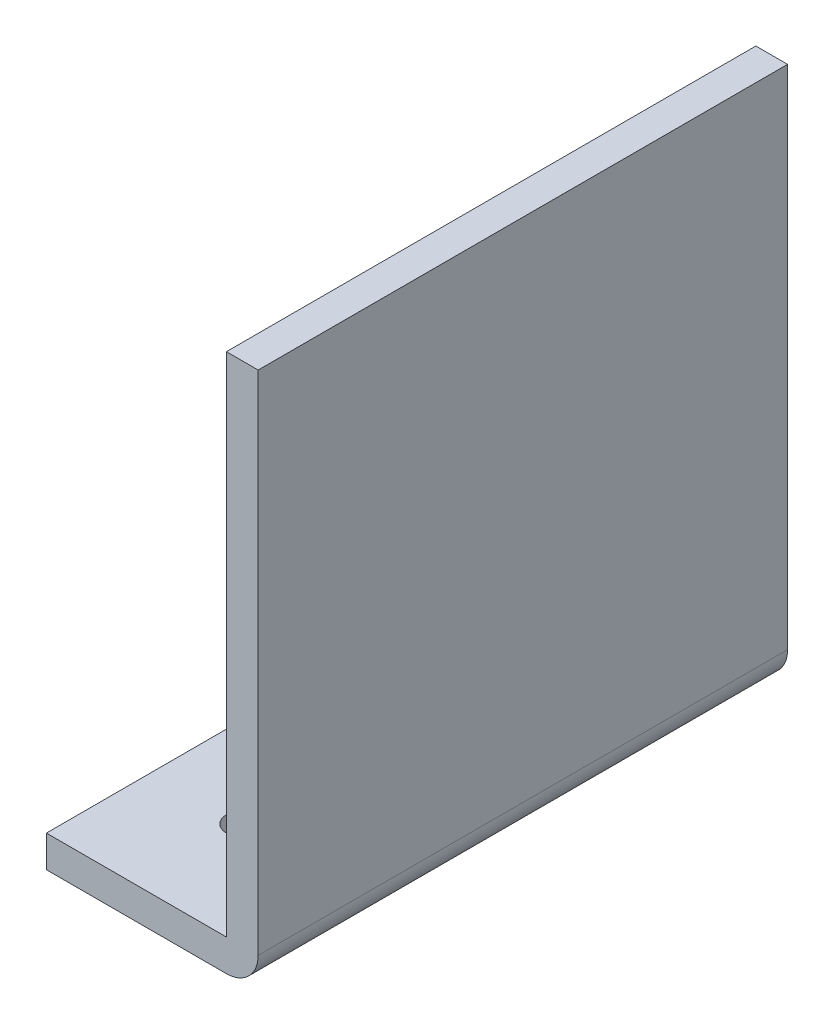
SolidWorks part; units mm, degrees
ref_plane "Plan de face" through (0, 0, 0) normal (0, 0, 1) x (1, 0, 0)
ref_plane "Plan de dessus" through (0, 0, 0) normal (0, 1, 0) x (1, 0, 0)
ref_plane "Plan de droite" through (0, 0, 0) normal (1, 0, 0) x (0, 0, -1)
sketch "Esquisse1" plane through (0, 0, 0) normal (0, 0, 1) x (1, 0, 0)
  line L0 (-20, 0) -> (-3, 0)
  line L1 (0, 3) -> (0, 50.87)
  line L2 (-20, 3) -> (-3, 3)
  line L3 (-3, 3) -> (-3, 50.87)
  line L4 (-3, 50.87) -> (0, 50.87)
  line L5 (-20, 3) -> (-20, 0)
  arc A0 (-3, 0) -> (0, 3) centre (-3, 3) ccw
  arc A1 (-3, 3) -> (-3, 3) centre (-3, 3) ccw
  point P6 (0, 0)
  dimension "D3" = 3
  dimension "D1" = 20
  dimension "D2" = 50.87
  dimension "D4" = 3
extrude "Boss.-Extru.1" add sketch "Esquisse1" along normal mid plane 50
sketch "Esquisse2" plane through (0, 3, 0) normal (0, 1, 0) x (1, 0, 0)
  line L0 (-11.5, 25) -> (-11.5, -25) construction
  line L1 (-3, 25) -> (-20, 25) construction
  line L2 (-3, -25) -> (-20, -25) construction
  circle A0 centre (-11.5, 15) radius 1.5
  circle A1 centre (-11.5, -15) radius 1.5
  point P10 (-11.5, 0)
  dimension "D1" = 3
  dimension "D2" = 3
  dimension "D3" = 15
  dimension "D4" = 15
extrude "Enlèv. mat.-Extru.1" cut sketch "Esquisse2" against normal blind 50
